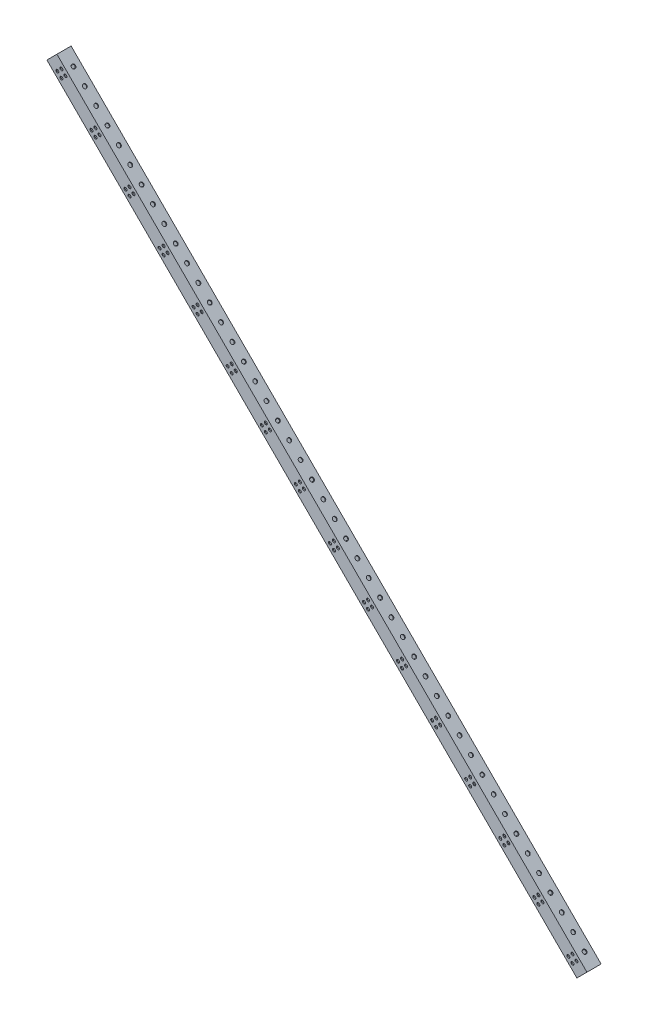
SolidWorks part; units mm, degrees
ref_plane "前视基准面" through (0, 0, 0) normal (0, 0, 1) x (1, 0, 0)
ref_plane "上视基准面" through (0, 0, 0) normal (0, 1, 0) x (1, 0, 0)
ref_plane "右视基准面" through (0, 0, 0) normal (1, 0, 0) x (0, 0, -1)
other "Configuration Table"
sketch "草图1" plane through (0, 0, 0) normal (0, 0, 1) x (1, 0, 0)
  line L0 (0, 560) -> (0, 0) construction
  line L1 (0, 0) -> (560, 0) construction
  line L2 (0, 0) -> (49.7921, 0) construction
  line L3 (5.3033, 565.3033) -> (-5.3033, 554.6967)
  line L8 (-5.3033, 554.6967) -> (554.6967, -5.3033)
  line L9 (554.6967, -5.3033) -> (565.3033, 5.3033)
  line L10 (565.3033, 5.3033) -> (5.3033, 565.3033)
  point P5 (0, 0)
  dimension "D1" = 90
  dimension "D2" = 560
  dimension "D3" = 560
  dimension "D4" = 15
extrude "凸台-拉伸1" add sketch "草图1" along normal blind 15
sketch "草图3" plane through (-280, 280, 0) normal (-0.7071, 0.7071, 0) x (0, 0, 1)
  line L0 (15, 403.4798) -> (0, 403.4798) construction
  line L1 (1, 389.4798) -> (14, 389.4798)
  line L2 (1, 389.4798) -> (1, 402.4798)
  line L3 (1, 402.4798) -> (14, 402.4798)
  line L4 (14, 389.4798) -> (14, 402.4798)
  line L5 (0, 403.4798) -> (0, 388.4798) construction
  dimension "D1" = 1
  dimension "D2" = 1
  dimension "D3" = 13
extrude "切除-拉伸2" cut sketch "草图3" against normal up to surface (791.9596 mm away) up to face at (560, 0, 7.5)
sketch "草图4" plane through (0, 0, 15) normal (0, 0, 1) x (1, 0, 0)
  line L0 (0, 560) -> (9.2347, 550.7653) construction
  line L2 (5.3033, 565.3033) -> (-5.3033, 554.6967) construction
  line L3 (-5.3033, 554.6967) -> (554.6967, -5.3033) construction
  line L4 (0, 560) -> (0, 540) construction
  line L5 (0, 540) -> (20, 540) construction
  circle A0 centre (5.7574, 550) radius 1.6
  circle A1 centre (10, 554.2426) radius 1.6
  circle A2 centre (10, 545.7574) radius 1.6
  circle A3 centre (14.2426, 550) radius 1.6
  circle A4 centre (41.7574, 514) radius 1.6
  circle A5 centre (46, 518.2426) radius 1.6
  circle A6 centre (50.2426, 514) radius 1.6
  circle A7 centre (46, 509.7574) radius 1.6
  circle A8 centre (77.7574, 478) radius 1.6
  circle A9 centre (82, 482.2426) radius 1.6
  circle A10 centre (86.2426, 478) radius 1.6
  circle A11 centre (82, 473.7574) radius 1.6
  circle A12 centre (113.7574, 442) radius 1.6
  circle A13 centre (118, 446.2426) radius 1.6
  circle A14 centre (122.2426, 442) radius 1.6
  circle A15 centre (118, 437.7574) radius 1.6
  circle A16 centre (149.7574, 406) radius 1.6
  circle A17 centre (154, 410.2426) radius 1.6
  circle A18 centre (158.2426, 406) radius 1.6
  circle A19 centre (154, 401.7574) radius 1.6
  circle A20 centre (185.7574, 370) radius 1.6
  circle A21 centre (190, 374.2426) radius 1.6
  circle A22 centre (194.2426, 370) radius 1.6
  circle A23 centre (190, 365.7574) radius 1.6
  circle A24 centre (221.7574, 334) radius 1.6
  circle A25 centre (226, 338.2426) radius 1.6
  circle A26 centre (230.2426, 334) radius 1.6
  circle A27 centre (226, 329.7574) radius 1.6
  circle A28 centre (257.7574, 298) radius 1.6
  circle A29 centre (262, 302.2426) radius 1.6
  circle A30 centre (266.2426, 298) radius 1.6
  circle A31 centre (262, 293.7574) radius 1.6
  circle A32 centre (293.7574, 262) radius 1.6
  circle A33 centre (298, 266.2426) radius 1.6
  circle A34 centre (302.2426, 262) radius 1.6
  circle A35 centre (298, 257.7574) radius 1.6
  circle A36 centre (329.7574, 226) radius 1.6
  circle A37 centre (334, 230.2426) radius 1.6
  circle A38 centre (338.2426, 226) radius 1.6
  circle A39 centre (334, 221.7574) radius 1.6
  circle A40 centre (365.7574, 190) radius 1.6
  circle A41 centre (370, 194.2426) radius 1.6
  circle A42 centre (374.2426, 190) radius 1.6
  circle A43 centre (370, 185.7574) radius 1.6
  circle A44 centre (401.7574, 154) radius 1.6
  circle A45 centre (406, 158.2426) radius 1.6
  circle A46 centre (410.2426, 154) radius 1.6
  circle A47 centre (406, 149.7574) radius 1.6
  circle A48 centre (437.7574, 118) radius 1.6
  circle A49 centre (442, 122.2426) radius 1.6
  circle A50 centre (446.2426, 118) radius 1.6
  circle A51 centre (442, 113.7574) radius 1.6
  circle A52 centre (473.7574, 82) radius 1.6
  circle A53 centre (478, 86.2426) radius 1.6
  circle A54 centre (482.2426, 82) radius 1.6
  circle A55 centre (478, 77.7574) radius 1.6
  circle A56 centre (509.7574, 46) radius 1.6
  circle A57 centre (514, 50.2426) radius 1.6
  circle A58 centre (518.2426, 46) radius 1.6
  circle A59 centre (514, 41.7574) radius 1.6
  circle A60 centre (545.7574, 10) radius 1.6
  circle A61 centre (550, 14.2426) radius 1.6
  circle A62 centre (554.2426, 10) radius 1.6
  circle A63 centre (550, 5.7574) radius 1.6
  dimension "D7" = 3.2
  dimension "D1" = 7.5
  dimension "D2" = 20
  dimension "D3" = 6
  dimension "D4" = 6
  dimension "D5" = 6
  dimension "D6" = 10
  dimension "D8" = 16
extrude "切除-拉伸3" cut sketch "草图4" against normal up to surface (15 mm away) up to face at (280, 280, 0)
sketch "草图5" plane through (274.6967, 274.6967, 0) normal (-0.7071, -0.7071, 0) x (0, 0, 1)
  line L0 (7.5, 395.9798) -> (7.5, 398.6945) construction
  line L2 (0, 395.9798) -> (0, -395.9798) construction
  line L3 (15, 395.9798) -> (0, 395.9798) construction
  circle A0 centre (7.5, 381.8377) radius 2.1
  circle A1 centre (7.5, 364.8671) radius 2.1
  circle A2 centre (7.5, 347.8965) radius 2.1
  circle A3 centre (7.5, 330.926) radius 2.1
  circle A4 centre (7.5, 313.9554) radius 2.1
  circle A5 centre (7.5, 296.9848) radius 2.1
  circle A6 centre (7.5, 280.0143) radius 2.1
  circle A7 centre (7.5, 263.0437) radius 2.1
  circle A8 centre (7.5, 246.0732) radius 2.1
  circle A9 centre (7.5, 229.1026) radius 2.1
  circle A10 centre (7.5, 212.132) radius 2.1
  circle A11 centre (7.5, 195.1615) radius 2.1
  circle A12 centre (7.5, 178.1909) radius 2.1
  circle A13 centre (7.5, 161.2203) radius 2.1
  circle A14 centre (7.5, 144.2498) radius 2.1
  circle A15 centre (7.5, 127.2792) radius 2.1
  circle A16 centre (7.5, 110.3087) radius 2.1
  circle A17 centre (7.5, 93.3381) radius 2.1
  circle A18 centre (7.5, 76.3675) radius 2.1
  circle A19 centre (7.5, 59.397) radius 2.1
  circle A20 centre (7.5, 42.4264) radius 2.1
  circle A21 centre (7.5, 25.4558) radius 2.1
  circle A22 centre (7.5, 8.4853) radius 2.1
  circle A23 centre (7.5, -8.4853) radius 2.1
  circle A24 centre (7.5, -25.4558) radius 2.1
  circle A25 centre (7.5, -42.4264) radius 2.1
  circle A26 centre (7.5, -59.397) radius 2.1
  circle A27 centre (7.5, -76.3675) radius 2.1
  circle A28 centre (7.5, -93.3381) radius 2.1
  circle A29 centre (7.5, -110.3087) radius 2.1
  circle A30 centre (7.5, -127.2792) radius 2.1
  circle A31 centre (7.5, -144.2498) radius 2.1
  circle A32 centre (7.5, -161.2203) radius 2.1
  circle A33 centre (7.5, -178.1909) radius 2.1
  circle A34 centre (7.5, -195.1615) radius 2.1
  circle A35 centre (7.5, -212.132) radius 2.1
  circle A36 centre (7.5, -229.1026) radius 2.1
  circle A37 centre (7.5, -246.0732) radius 2.1
  circle A38 centre (7.5, -263.0437) radius 2.1
  circle A39 centre (7.5, -280.0143) radius 2.1
  circle A40 centre (7.5, -296.9848) radius 2.1
  circle A41 centre (7.5, -313.9554) radius 2.1
  circle A42 centre (7.5, -330.926) radius 2.1
  circle A43 centre (7.5, -347.8965) radius 2.1
  circle A44 centre (7.5, -364.8671) radius 2.1
  circle A45 centre (7.5, -381.8377) radius 2.1
  dimension "D2" = 4.2
  dimension "D1" = 7.5
  dimension "D3" = 14.1421
  dimension "D4" = 46
extrude "切除-拉伸4" cut sketch "草图5" against normal up to surface (15 mm away) up to face at (285.3033, 285.3033, 7.5)
